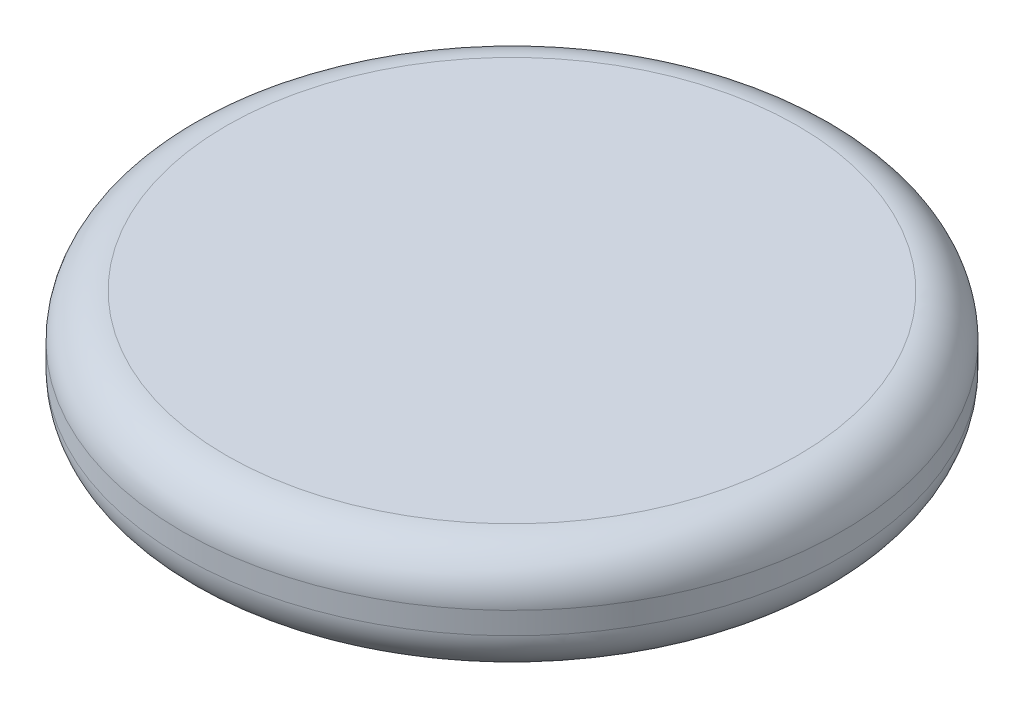
SolidWorks part; units mm, degrees
ref_plane "Front Plane" through (0, 0, 0) normal (0, 0, 1) x (1, 0, 0)
ref_plane "Top Plane" through (0, 0, 0) normal (0, 1, 0) x (1, 0, 0)
ref_plane "Right Plane" through (0, 0, 0) normal (1, 0, 0) x (0, 0, -1)
sketch "Sketch2" plane through (0, 0, 0) normal (0, 1, 0) x (1, 0, 0)
  circle A0 centre (0, 0) radius 75
extrude "Boss-Extrude1" add sketch "Sketch2" along normal blind 25
fillet "Fillet1" radius 10 2 edges at (0, 0, 75) (0, 25, 75)
scale "Scale1" scale about origin uniform scaling yes scale factor 0.333333
